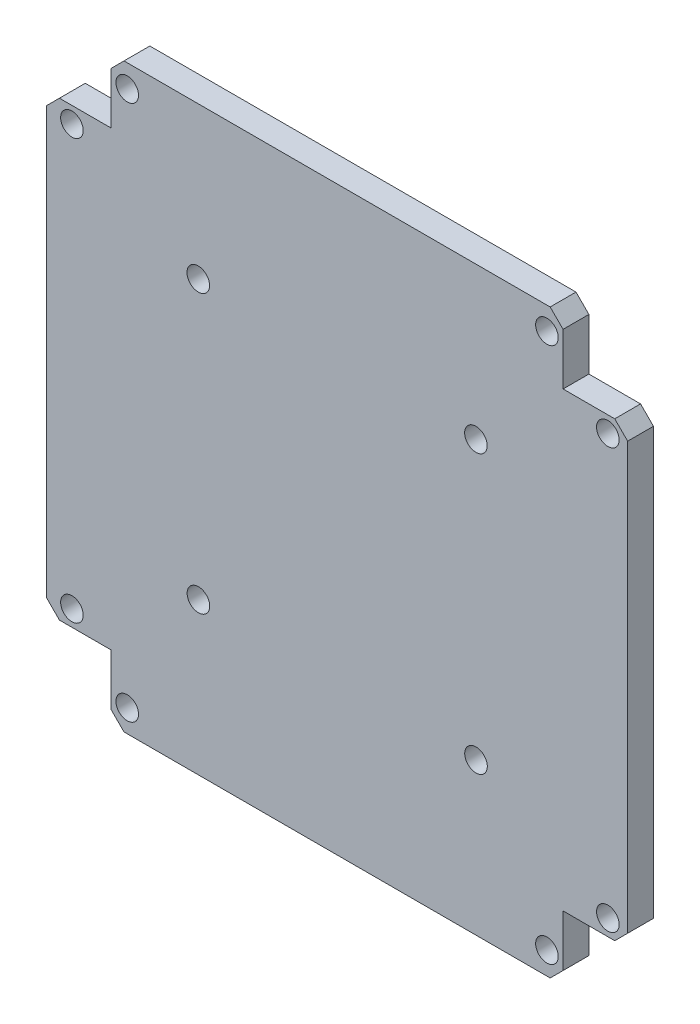
SolidWorks part; units mm, degrees
ref_plane "Plan de face" through (0, 0, 0) normal (0, 0, 1) x (1, 0, 0)
ref_plane "Plan de dessus" through (0, 0, 0) normal (0, 1, 0) x (1, 0, 0)
ref_plane "Plan de droite" through (0, 0, 0) normal (1, 0, 0) x (0, 0, -1)
sketch "Sketch1" plane through (0, 0, 0) normal (0, 0, 1) x (1, 0, 0)
  line L1 (-0.2317, 0.1934) -> (89.7683, 0.1934)
  line L2 (-0.2317, 0.1934) -> (-0.2317, 70.1934)
  line L3 (-0.2317, 70.1934) -> (89.7683, 70.1934)
  line L4 (89.7683, 0.1934) -> (89.7683, 70.1934)
  dimension "D1" = 70
  dimension "D2" = 90
extrude "Boss-Extrude1" add sketch "Sketch1" along normal blind 4
sketch "Sketch2" plane through (0, 0, 4) normal (0, 0, 1) x (1, 0, 0)
  line L0 (89.7683, 70.1934) -> (-0.2317, 70.1934) construction
  line L6 (-0.2317, 70.1934) -> (-0.2317, 0.1934) construction
  line L7 (89.7683, 0.1934) -> (89.7683, 70.1934) construction
  line L9 (-0.2317, 0.1934) -> (89.7683, 0.1934) construction
  circle A0 centre (3.7036, 2.6934) radius 1.75
  circle A1 centre (86.7036, 2.6944) radius 1.75
  circle A2 centre (86.7033, 67.6934) radius 1.75
  circle A3 centre (3.7033, 67.6934) radius 1.75
  circle A4 centre (23.2977, 13.6934) radius 1.75
  circle A5 centre (66.2841, 13.6934) radius 1.75
  circle A6 centre (66.2683, 56.6934) radius 1.75
  circle A7 centre (23.2683, 56.6934) radius 1.75
  dimension "D7" = 3.5
  dimension "D8" = 3.5
  dimension "D9" = 3.5
  dimension "D10" = 3.5
  dimension "D22" = 3.5
  dimension "D23" = 3.5
  dimension "D24" = 3.5
  dimension "D25" = 3.5
  dimension "D3" = 3.065
  dimension "D4" = 83
  dimension "D5" = 2.5
  dimension "D6" = 2.5
  dimension "D15" = 13.5
  dimension "D16" = 23.5295
  dimension "D17" = 13.5
  dimension "D18" = 13.5
  dimension "D19" = 23.5
  dimension "D20" = 13.5
  dimension "D21" = 23.5
extrude "Cut-Extrude1" cut sketch "Sketch2" against normal blind 5
chamfer "Chamfer1" distance 2 angle 45 1 edges at (89.7683, 0.1934, 2)
chamfer "Chamfer2" distance 2 angle 45 1 edges at (-0.2317, 0.1934, 2)
chamfer "Chamfer3" distance 2 angle 45 1 edges at (-0.2317, 70.1934, 2)
chamfer "Chamfer4" distance 2 angle 45 1 edges at (89.7683, 70.1934, 2)
sketch "Sketch4" plane through (0, 0.1934, 0) normal (0, -1, 0) x (-1, 0, 0)
  line L0 (-1.7683, 0) -> (-87.7683, 0) construction
  line L1 (-9.7683, -4) -> (-79.7683, -4)
  line L2 (-9.7683, -4) -> (-9.7683, 0)
  line L3 (-9.7683, 0) -> (-79.7683, 0)
  line L4 (-79.7683, -4) -> (-79.7683, 0)
  dimension "D1" = 70
  dimension "D2" = 8
  dimension "D3" = 4
  dimension "D4" = 0
sketch "Sketch5" plane through (0, 70.1934, 0) normal (0, 1, 0) x (1, 0, 0)
  line L0 (87.7683, 0) -> (1.7683, 0) construction
  line L1 (9.7683, -4) -> (79.7683, -4)
  line L2 (9.7683, -4) -> (9.7683, 0)
  line L3 (9.7683, 0) -> (79.7683, 0)
  line L4 (79.7683, -4) -> (79.7683, 0)
  dimension "D1" = 70
  dimension "D2" = 8
  dimension "D3" = 4
  dimension "D4" = 0
extrude "Boss-Extrude3" add sketch "Sketch5" along normal blind 10
extrude "Boss-Extrude4" add sketch "Sketch4" along normal blind 10
sketch "Sketch6" plane through (0, 0, 0) normal (0, 0, -1) x (-1, 0, 0)
  line L0 (-79.7683, 80.1934) -> (-79.7683, 70.1934) construction
  line L2 (-79.7683, -9.8066) -> (-79.7683, 0.1934) construction
  line L5 (-79.7683, 80.1934) -> (-9.7683, 80.1934) construction
  circle A0 centre (-12.2683, 76.6934) radius 1.75
  circle A1 centre (-77.2683, 76.6934) radius 1.75
  circle A2 centre (-77.2683, -6.3066) radius 1.75
  circle A3 centre (-12.2683, -6.3066) radius 1.75
  dimension "D7" = 3.5
  dimension "D8" = 3.5
  dimension "D9" = 3.5
  dimension "D10" = 3.5
  dimension "D1" = 83
  dimension "D2" = 83
  dimension "D3" = 65
  dimension "D4" = 65
  dimension "D5" = 2.5
  dimension "D6" = 2.5
  dimension "D11" = 3.5
  dimension "D12" = 3.5
extrude "Cut-Extrude2" cut sketch "Sketch6" against normal blind 10
chamfer "Chamfer5" distance 2 angle 45 4 edges at (9.7683, -9.8066, 2) (79.7683, -9.8066, 2) (9.7683, 80.1934, 2) (79.7683, 80.1934, 2)
